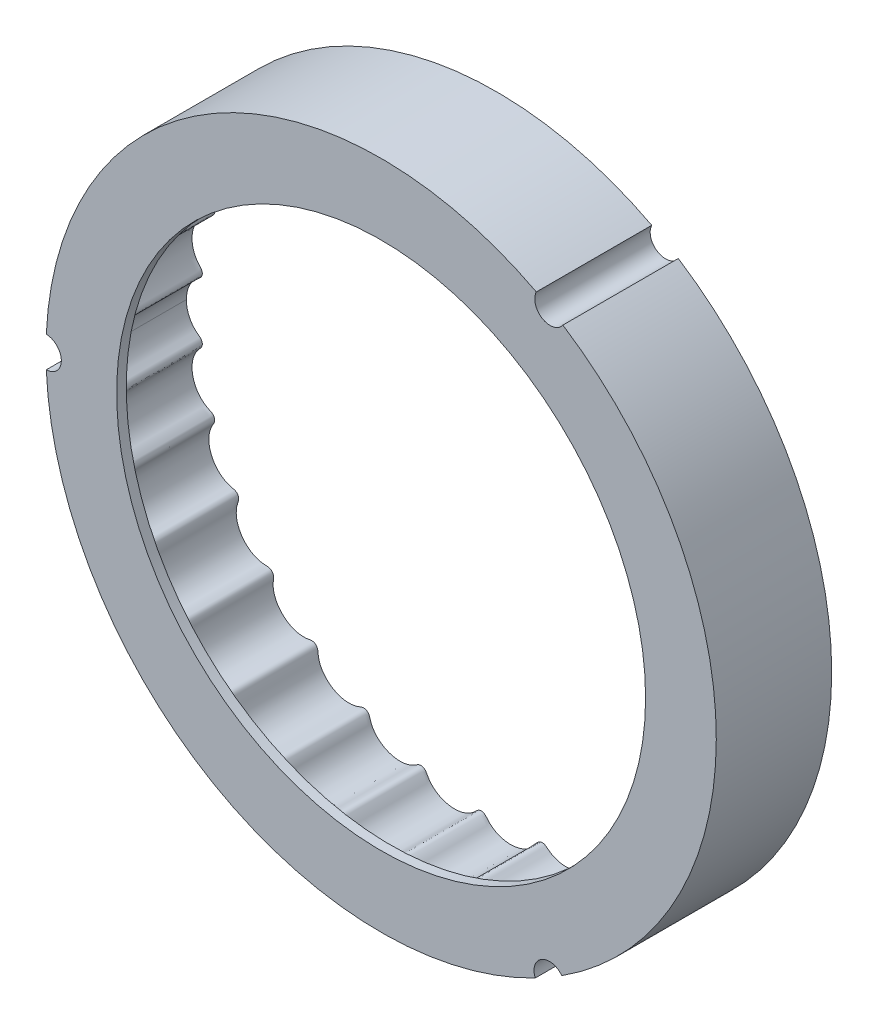
SolidWorks part; units mm, degrees
ref_plane "Plan de face" through (0, 0, 0) normal (0, 0, 1) x (1, 0, 0)
ref_plane "Plan de dessus" through (0, 0, 0) normal (0, 1, 0) x (1, 0, 0)
ref_plane "Plan de droite" through (0, 0, 0) normal (1, 0, 0) x (0, 0, -1)
sketch "Esquisse1" plane through (0, 0, 0) normal (0, 0, 1) x (1, 0, 0)
  line L0 (-1000, 0) -> (49000, 0) construction
  circle A1 centre (0, 0) radius 34.85
  spline S0 degree 4 poles (30.9263, 8.5917) (30.9244, 8.4726) (30.9128, 8.294) (30.8795, 8.0576) (30.8075, 7.7682) (30.7313, 7.5422) (30.6363, 7.3233) (30.5223, 7.1138) (30.4005, 6.9287) (30.2778, 6.7655) (30.1754, 6.608) (30.1146, 6.4469) (30.0971, 6.2542) (30.1421, 6.0755) (30.2337, 5.9301) (30.3636, 5.8076) (30.4814, 5.7308) (30.5967, 5.6632) (30.7272, 5.5824) (30.8546, 5.4968) (31.0375, 5.3568) (31.2617, 5.1464) (31.5493, 4.8022) (31.8437, 4.2901) (32.0606, 3.6436) (32.1377, 2.876) (32.0537, 2.1997) (31.8673, 1.6401) (31.6545, 1.2467) (31.4775, 0.9968) (31.3101, 0.8048) (31.1655, 0.661) (31.0397, 0.5491) (30.944, 0.4561) (30.882, 0.3799) (30.8461, 0.3281) (30.8149, 0.2732) (30.7893, 0.2154) (30.772, 0.1642) (30.7612, 0.1176) (30.7537, 0.0676) (30.7495, 0.0174) (30.7494, -0.0196) (30.7554, -0.0873) (30.767, -0.1466) (30.7842, -0.2016) (30.8067, -0.2559) (30.8409, -0.3211) (30.8874, -0.3891) (30.9471, -0.4581) (31.0185, -0.528) (31.0876, -0.5916) (31.174, -0.6713) (31.275, -0.7696) (31.4187, -0.925) (31.5905, -1.1493) (31.7652, -1.4406) (31.9227, -1.8045) (32.035, -2.1949) (32.0985, -2.6058) (32.1109, -3.0185) (32.074, -3.4266) (31.9897, -3.8245) (31.8596, -4.2068) (31.6858, -4.5663) (31.471, -4.8977) (31.2491, -5.1584) (31.0376, -5.3559) (30.847, -5.5028) (30.6865, -5.6097) (30.5113, -5.713) (30.3279, -5.8265) (30.1731, -5.9986) (30.0932, -6.2291) (30.1102, -6.46) (30.2005, -6.6565) (30.3192, -6.8188) (30.4296, -6.9724) (30.5569, -7.1717) (30.687, -7.4243) (30.8105, -7.7521) (30.9023, -8.158) (30.9393, -8.591) (30.9154, -9.0432) (30.8331, -9.4792) (30.6986, -9.8922) (30.5175, -10.2769) (30.2954, -10.6287) (30.0366, -10.942) (29.747, -11.2129) (29.4704, -11.4101) (29.2233, -11.5472) (29.008, -11.6414) (28.8315, -11.7068) (28.6421, -11.7692) (28.45, -11.8631) (28.2883, -12.027) (28.2103, -12.2249) (28.2035, -12.4054) (28.2368, -12.5701) (28.2938, -12.7158) (28.368, -12.8732) (28.4417, -13.0514) (28.5193, -13.2794) (28.5859, -13.5612) (28.6259, -13.9014) (28.6202, -14.2968) (28.5642, -14.6927) (28.4589, -15.0831) (28.3079, -15.4581) (28.1138, -15.8126) (27.8795, -16.1417) (27.6077, -16.4405) (27.3049, -16.7011) (26.9756, -16.9193) (26.6681, -17.0697) (26.3953, -17.1663) (26.1618, -17.2248) (25.972, -17.2589) (25.7701, -17.2839) (25.5569, -17.3186) (25.349, -17.4213) (25.1897, -17.6061) (25.1202, -17.827) (25.1307, -18.0426) (25.1768, -18.2381) (25.2169, -18.423) (25.254, -18.6564) (25.2723, -18.9399) (25.2546, -19.2896) (25.1768, -19.6983) (25.0382, -20.11) (24.8361, -20.5151) (24.5838, -20.8868) (24.2876, -21.2199) (23.9535, -21.5097) (23.5874, -21.7517) (23.2101, -21.9337) (22.8739, -22.0436) (22.5914, -22.1021) (22.3252, -22.1336) (22.1016, -22.1407) (21.8785, -22.1275) (21.6437, -22.1096) (21.4389, -22.1288) (21.235, -22.2214) (21.0721, -22.3967) (20.993, -22.6129) (20.9856, -22.8294) (20.9927, -23.0328) (20.9891, -23.2256) (20.9691, -23.4656) (20.9175, -23.7504) (20.8184, -24.0782) (20.6555, -24.4384) (20.4463, -24.779) (20.1313, -25.174) (19.6816, -25.5833) (19.1591, -25.8987) (18.5904, -26.1016) (18.1017, -26.1879) (17.7596, -26.203) (17.4709, -26.1826) (17.2335, -26.1428) (17.0458, -26.0984) (16.8505, -26.0411) (16.6399, -25.9918) (16.4106, -26.0101) (16.1979, -26.12) (16.0541, -26.2917) (15.9812, -26.4843) (15.9468, -26.6722) (15.9136, -26.8477) (15.8717, -27.0214) (15.8184, -27.1921) (15.7382, -27.4006) (15.5637, -27.7585) (15.2945, -28.1386) (14.9171, -28.5115) (14.4633, -28.8259) (14.0673, -29.0303) (13.6447, -29.1826) (13.2023, -29.278) (12.7692, -29.3104) (12.354, -29.2847) (12.0109, -29.2154) (11.7407, -29.1278) (11.5237, -29.0341) (11.3545, -28.9495) (11.1772, -28.8554) (10.9723, -28.7881) (10.7409, -28.7959) (10.5202, -28.8997) (10.3654, -29.0728) (10.2765, -29.2698) (10.2021, -29.4592) (10.1221, -29.6346) (10.0078, -29.8465) (9.8467, -30.087) (9.625, -30.3479) (9.2571, -30.6809) (8.748, -31.0055) (8.1785, -31.2248) (7.5795, -31.329) (7.0742, -31.3356) (6.6768, -31.2918) (6.2924, -31.1996) (5.9727, -31.0767) (5.7161, -30.9427) (5.5144, -30.8112) (5.3599, -30.6957) (5.2035, -30.5655) (5.0269, -30.4397) (4.8069, -30.3718) (4.5688, -30.3956) (4.3717, -30.5019) (4.2324, -30.653) (4.1276, -30.8125) (4.0272, -30.9603) (3.9195, -31.1029) (3.8025, -31.238) (3.6457, -31.3971) (3.3428, -31.6554) (2.8502, -31.9535) (2.2369, -32.1596) (1.5733, -32.2322) (1.0155, -32.1965) (0.5716, -32.1077) (0.1613, -31.9647) (-0.2092, -31.7754) (-0.4962, -31.5747) (-0.7089, -31.3863) (-0.8705, -31.2138) (-0.9919, -31.0688) (-1.1186, -30.9128) (-1.2838, -30.7736) (-1.5018, -30.6954) (-1.7453, -30.7105) (-1.9528, -30.8138) (-2.1099, -30.9617) (-2.2535, -31.1059) (-2.3968, -31.2349) (-2.5863, -31.3834) (-2.8299, -31.5395) (-3.1373, -31.6901) (-3.5116, -31.8163) (-3.9031, -31.8956) (-4.3058, -31.9269) (-4.7094, -31.9102) (-5.1084, -31.8461) (-5.4973, -31.7354) (-5.8703, -31.5791) (-6.2174, -31.3804) (-6.5332, -31.1424) (-6.7773, -30.902) (-6.9589, -30.6765) (-7.0914, -30.4753) (-7.1869, -30.3078) (-7.2659, -30.1527) (-7.3469, -30.0188) (-7.4577, -29.8924) (-7.6055, -29.7886) (-7.8103, -29.7311) (-8.0386, -29.7607) (-8.2296, -29.8563) (-8.3948, -29.9679) (-8.5547, -30.0672) (-8.7612, -30.1794) (-9.0211, -30.2905) (-9.3464, -30.3878) (-9.7381, -30.4504) (-10.1442, -30.4625) (-10.5582, -30.4222) (-10.9731, -30.3294) (-11.3818, -30.1823) (-11.7767, -29.98) (-12.1486, -29.7215) (-12.4679, -29.4266) (-12.7322, -29.1051) (-12.9152, -28.8064) (-13.0349, -28.5486) (-13.1142, -28.3258) (-13.1678, -28.1444) (-13.224, -27.9513) (-13.3256, -27.7603) (-13.4992, -27.6071) (-13.731, -27.5313) (-13.9616, -27.5503) (-14.1632, -27.6266) (-14.3522, -27.7017) (-14.535, -27.7628) (-14.7681, -27.8232) (-15.0538, -27.869) (-15.3957, -27.8843) (-15.7892, -27.8507) (-16.2785, -27.7463) (-16.7528, -27.5609) (-17.1946, -27.3015) (-17.5907, -26.9743) (-17.8764, -26.672) (-18.1159, -26.3439) (-18.3067, -25.9962) (-18.4295, -25.6796) (-18.5013, -25.4063) (-18.5394, -25.1743) (-18.559, -24.9871) (-18.5718, -24.7882) (-18.6117, -24.5785) (-18.7262, -24.3789) (-18.8959, -24.2506) (-19.068, -24.1957) (-19.2358, -24.1842) (-19.3915, -24.2014) (-19.5625, -24.2339) (-19.7534, -24.2613) (-19.9935, -24.2801) (-20.283, -24.2751) (-20.6226, -24.2297) (-21.0043, -24.1264) (-21.3741, -23.9741) (-21.7265, -23.7753) (-22.0523, -23.536) (-22.3477, -23.2602) (-22.6084, -22.9516) (-22.8306, -22.6144) (-23.008, -22.2566) (-23.138, -21.8836) (-23.2077, -21.5484) (-23.2339, -21.2603) (-23.2329, -21.0195) (-23.2189, -20.8273) (-23.1931, -20.6255) (-23.1714, -20.4109) (-23.2147, -20.1833) (-23.35, -19.9802) (-23.5441, -19.854) (-23.755, -19.8069) (-23.956, -19.8018) (-24.145, -19.7948) (-24.3804, -19.7731) (-24.6597, -19.7208) (-25.1025, -19.5837) (-25.5719, -19.3339) (-26.0033, -18.993) (-26.3759, -18.5716) (-26.6251, -18.2022) (-26.8231, -17.8067) (-26.9668, -17.3922) (-27.0498, -16.9817) (-27.0732, -16.6288) (-27.06, -16.3406) (-27.0307, -16.1192) (-26.9958, -15.9439) (-26.9493, -15.7714) (-26.894, -15.6014) (-26.8318, -15.421) (-26.7962, -15.2188) (-26.8307, -14.9976) (-26.9558, -14.7937) (-27.1431, -14.6595) (-27.3504, -14.5957) (-27.5492, -14.5518) (-27.7351, -14.5006) (-27.9627, -14.422) (-28.2261, -14.3016) (-28.5192, -14.1246) (-28.8279, -13.8775) (-29.1063, -13.5905) (-29.4109, -13.1873) (-29.6486, -12.7398) (-29.8135, -12.2607) (-29.9002, -11.7631) (-29.9203, -11.3641) (-29.8906, -10.9701) (-29.8207, -10.6349) (-29.7296, -10.3602) (-29.6324, -10.14) (-29.543, -9.9692) (-29.4389, -9.7943) (-29.3367, -9.6039) (-29.2926, -9.3762) (-29.3434, -9.1376) (-29.4773, -8.9486) (-29.655, -8.8263) (-29.838, -8.7434) (-30.0085, -8.6617) (-30.2156, -8.5478) (-30.4507, -8.3882) (-30.716, -8.1598) (-30.9909, -7.8477) (-31.231, -7.4857) (-31.427, -7.0776) (-31.5659, -6.6505) (-31.6473, -6.2122) (-31.6713, -5.7706) (-31.638, -5.3329) (-31.5503, -4.9233) (-31.4308, -4.5902) (-31.3037, -4.3313) (-31.1883, -4.14) (-31.0862, -3.9932) (-30.9747, -3.8536) (-30.8564, -3.7197) (-30.7286, -3.5777) (-30.6197, -3.4032) (-30.57, -3.1848) (-30.6111, -2.949) (-30.7353, -2.7553) (-30.9027, -2.6179) (-31.0677, -2.4988) (-31.2178, -2.3777) (-31.395, -2.2147) (-31.5882, -1.9992) (-31.757, -1.7611) (-31.8999, -1.5043) (-32.0017, -1.2787) (-32.0729, -1.0898) (-32.1322, -0.8972) (-32.1797, -0.7008) (-32.2109, -0.5276) (-32.2302, -0.3771) (-32.2413, -0.2512) (-32.2473, -0.1576) (-32.2503, -0.0299) (-32.2502, 0.0388) (-32.2466, 0.1794) (-32.2393, 0.2769) (-32.2254, 0.4211) (-32.2015, 0.5861) (-32.1629, 0.7796) (-32.104, 0.996) (-32.0305, 1.2085) (-31.9423, 1.415) (-31.8234, 1.6465) (-31.6896, 1.8577) (-31.544, 2.0481) (-31.3892, 2.217) (-31.2566, 2.3437) (-31.1158, 2.461) (-30.9692, 2.571) (-30.8116, 2.6874) (-30.6684, 2.8431) (-30.5791, 3.0569) (-30.5824, 3.2743) (-30.648, 3.4491) (-30.7462, 3.5961) (-30.8554, 3.7195) (-30.9782, 3.8564) (-31.1043, 4.0167) (-31.2467, 4.228) (-31.3916, 4.4977) (-31.5524, 4.9075) (-31.6691, 5.4709) (-31.6776, 6.1306) (-31.5281, 6.8579) (-31.2314, 7.526) (-30.8027, 8.104) (-30.3929, 8.4476) (-30.0923, 8.62) (-29.937, 8.6951) knots 0 0 0 0 0 0.003562 0.005342 0.007123 0.008904 0.010685 0.012466 0.014247 0.015519 0.016792 0.018065 0.019337 0.021229 0.022175 0.02312 0.024649 0.025414 0.026178 0.027707 0.029236 0.032293 0.035351 0.04107 0.046788 0.052507 0.058226 0.06127 0.064314 0.065836 0.067358 0.06888 0.070402 0.070873 0.071343 0.071813 0.072284 0.072754 0.073224 0.073459 0.073695 0.074165 0.074604 0.075042 0.075481 0.07592 0.076358 0.076797 0.077674 0.078377 0.079079 0.079782 0.080484 0.081889 0.083294 0.086104 0.088914 0.092014 0.095114 0.098215 0.101315 0.104325 0.107336 0.110347 0.113357 0.116235 0.119112 0.12055 0.121989 0.123428 0.124866 0.12664 0.128414 0.130187 0.13196 0.133373 0.134786 0.1362 0.137613 0.140439 0.143265 0.146639 0.150014 0.153388 0.156763 0.159865 0.162966 0.166068 0.169169 0.171979 0.174789 0.176194 0.177599 0.179004 0.180409 0.182167 0.183924 0.185706 0.186596 0.187487 0.188927 0.190366 0.191805 0.193245 0.196124 0.199002 0.202017 0.205033 0.208048 0.211063 0.214074 0.217086 0.220098 0.22311 0.225987 0.228865 0.230303 0.231742 0.233181 0.234619 0.236396 0.238172 0.239944 0.241716 0.243129 0.244541 0.245954 0.247367 0.250192 0.253017 0.256391 0.259764 0.263137 0.266511 0.269782 0.273052 0.276323 0.279594 0.282264 0.283598 0.284933 0.287603 0.288938 0.290273 0.291978 0.293684 0.295463 0.297243 0.298682 0.300121 0.30156 0.302999 0.305877 0.308756 0.311769 0.314783 0.317797 0.323824 0.32985 0.332862 0.33574 0.338618 0.340058 0.341497 0.342936 0.344375 0.346152 0.34793 0.349637 0.351344 0.352679 0.354014 0.355349 0.356684 0.358019 0.359354 0.362024 0.368567 0.371839 0.375111 0.378483 0.381856 0.385228 0.388601 0.391426 0.39425 0.395663 0.397075 0.398488 0.3999 0.401672 0.403443 0.40522 0.406997 0.408436 0.409875 0.411314 0.412753 0.415631 0.418509 0.421521 0.427546 0.433573 0.436587 0.439601 0.442616 0.445494 0.448372 0.449812 0.451251 0.45269 0.454129 0.455909 0.457689 0.459394 0.461099 0.462434 0.463768 0.465103 0.466438 0.467773 0.469108 0.471777 0.478318 0.484859 0.488232 0.491606 0.49498 0.498354 0.501179 0.504005 0.505418 0.50683 0.508243 0.509656 0.511429 0.513201 0.514977 0.516752 0.518191 0.519629 0.521068 0.522507 0.525384 0.528261 0.531273 0.534284 0.537295 0.540307 0.543322 0.546338 0.549353 0.552369 0.555248 0.558127 0.559566 0.561006 0.562445 0.563885 0.564776 0.565667 0.567449 0.569206 0.570963 0.572368 0.573772 0.575177 0.576582 0.579392 0.582202 0.585303 0.588404 0.591505 0.594606 0.597981 0.601356 0.604731 0.608106 0.610932 0.613759 0.615172 0.616585 0.617999 0.619412 0.621185 0.622958 0.624731 0.626505 0.627943 0.629382 0.63082 0.632259 0.635136 0.638013 0.641024 0.644034 0.650055 0.653155 0.656256 0.659357 0.662457 0.665267 0.668077 0.669482 0.670887 0.672292 0.673697 0.675453 0.677208 0.678992 0.679883 0.680775 0.682214 0.683654 0.685093 0.686533 0.689412 0.69229 0.695306 0.698322 0.701338 0.704354 0.707365 0.710376 0.713387 0.716398 0.719275 0.722153 0.723591 0.72503 0.726469 0.727907 0.729682 0.731457 0.73323 0.735002 0.736415 0.737828 0.739241 0.740654 0.74348 0.746306 0.753054 0.756428 0.759802 0.763072 0.766342 0.769612 0.772882 0.775551 0.776886 0.778221 0.779556 0.780891 0.782226 0.78356 0.785264 0.786968 0.788749 0.790529 0.791969 0.793408 0.794847 0.796287 0.799165 0.802044 0.805058 0.808073 0.811088 0.817114 0.820127 0.823139 0.826151 0.829028 0.831906 0.833345 0.834784 0.836223 0.837661 0.839438 0.841215 0.842986 0.844758 0.846171 0.847583 0.848996 0.850409 0.853234 0.856059 0.859432 0.862805 0.866178 0.86955 0.872822 0.876093 0.879364 0.882635 0.885305 0.88664 0.887975 0.88931 0.890645 0.89198 0.893315 0.895021 0.896727 0.898506 0.900284 0.901724 0.903163 0.904602 0.906041 0.908919 0.911797 0.913304 0.91481 0.916317 0.917824 0.91933 0.920837 0.92159 0.922344 0.923097 0.92385 0.924689 0.925528 0.926367 0.927206 0.928883 0.930561 0.932238 0.933916 0.935594 0.937271 0.94001 0.941379 0.942748 0.944117 0.945486 0.946856 0.948225 0.949976 0.951727 0.9536 0.954537 0.955474 0.956996 0.958518 0.96004 0.961563 0.964607 0.967651 0.973159 0.978666 0.984174 0.989682 0.994841 1 1 1 1 1 construction
  spline S1 degree 4 poles (30.75, 0) (30.75, -0.0125) (30.751, -0.0374) (30.7554, -0.0873) (30.767, -0.1466) (30.7842, -0.2016) (30.8067, -0.2559) (30.8409, -0.3211) (30.8874, -0.3891) (30.9471, -0.4581) (31.0185, -0.528) (31.0876, -0.5916) (31.174, -0.6713) (31.275, -0.7696) (31.4187, -0.925) (31.5905, -1.1493) (31.7652, -1.4406) (31.9227, -1.8045) (32.035, -2.1949) (32.0985, -2.6058) (32.1109, -3.0185) (32.074, -3.4266) (31.9897, -3.8245) (31.8596, -4.2068) (31.6858, -4.5663) (31.471, -4.8977) (31.2491, -5.1584) (31.0376, -5.3559) (30.847, -5.5028) (30.6865, -5.6097) (30.5113, -5.713) (30.3279, -5.8265) (30.1731, -5.9986) (30.0932, -6.2291) (30.1102, -6.46) (30.2005, -6.6565) (30.3192, -6.8188) (30.4296, -6.9724) (30.5569, -7.1717) (30.687, -7.4243) (30.8105, -7.7521) (30.9023, -8.158) (30.9393, -8.591) (30.9154, -9.0432) (30.8331, -9.4792) (30.6986, -9.8922) (30.5175, -10.2769) (30.2954, -10.6287) (30.0366, -10.942) (29.747, -11.2129) (29.4704, -11.4101) (29.2233, -11.5472) (29.008, -11.6414) (28.8315, -11.7068) (28.6421, -11.7692) (28.45, -11.8631) (28.2883, -12.027) (28.2103, -12.2249) (28.2035, -12.4054) (28.2368, -12.5701) (28.2938, -12.7158) (28.368, -12.8732) (28.4417, -13.0514) (28.5193, -13.2794) (28.5859, -13.5612) (28.6259, -13.9014) (28.6202, -14.2968) (28.5642, -14.6927) (28.4589, -15.0831) (28.3079, -15.4581) (28.1138, -15.8126) (27.8795, -16.1417) (27.6077, -16.4405) (27.3049, -16.7011) (26.9756, -16.9193) (26.6681, -17.0697) (26.3953, -17.1663) (26.1618, -17.2248) (25.972, -17.2589) (25.7701, -17.2839) (25.5569, -17.3186) (25.349, -17.4213) (25.1897, -17.6061) (25.1202, -17.827) (25.1307, -18.0426) (25.1768, -18.2381) (25.2169, -18.423) (25.254, -18.6564) (25.2723, -18.9399) (25.2546, -19.2896) (25.1768, -19.6983) (25.0382, -20.11) (24.8361, -20.5151) (24.5838, -20.8868) (24.2876, -21.2199) (23.9535, -21.5097) (23.5874, -21.7517) (23.2101, -21.9337) (22.8739, -22.0436) (22.5914, -22.1021) (22.3252, -22.1336) (22.1016, -22.1407) (21.8785, -22.1275) (21.6437, -22.1096) (21.4389, -22.1288) (21.235, -22.2214) (21.0721, -22.3967) (20.993, -22.6129) (20.9856, -22.8294) (20.9927, -23.0328) (20.9891, -23.2256) (20.9691, -23.4656) (20.9175, -23.7504) (20.8184, -24.0782) (20.6555, -24.4384) (20.4463, -24.779) (20.1313, -25.174) (19.6816, -25.5833) (19.1591, -25.8987) (18.5904, -26.1016) (18.1017, -26.1879) (17.7596, -26.203) (17.4709, -26.1826) (17.2335, -26.1428) (17.0458, -26.0984) (16.8505, -26.0411) (16.6399, -25.9918) (16.4106, -26.0101) (16.1979, -26.12) (16.0541, -26.2917) (15.9812, -26.4843) (15.9468, -26.6722) (15.9136, -26.8477) (15.8717, -27.0214) (15.8184, -27.1921) (15.7382, -27.4006) (15.5637, -27.7585) (15.2945, -28.1386) (14.9171, -28.5115) (14.4633, -28.8259) (14.0673, -29.0303) (13.6447, -29.1826) (13.2023, -29.278) (12.7692, -29.3104) (12.354, -29.2847) (12.0109, -29.2154) (11.7407, -29.1278) (11.5237, -29.0341) (11.3545, -28.9495) (11.1772, -28.8554) (10.9723, -28.7881) (10.7409, -28.7959) (10.5202, -28.8997) (10.3654, -29.0728) (10.2765, -29.2698) (10.2021, -29.4592) (10.1221, -29.6346) (10.0078, -29.8465) (9.8467, -30.087) (9.625, -30.3479) (9.2571, -30.6809) (8.748, -31.0055) (8.1785, -31.2248) (7.5795, -31.329) (7.0742, -31.3356) (6.6768, -31.2918) (6.2924, -31.1996) (5.9727, -31.0767) (5.7161, -30.9427) (5.5144, -30.8112) (5.3599, -30.6957) (5.2035, -30.5655) (5.0269, -30.4397) (4.8069, -30.3718) (4.5688, -30.3956) (4.3717, -30.5019) (4.2324, -30.653) (4.1276, -30.8125) (4.0272, -30.9603) (3.9195, -31.1029) (3.8025, -31.238) (3.6457, -31.3971) (3.3428, -31.6554) (2.8502, -31.9535) (2.2369, -32.1596) (1.5733, -32.2322) (1.0155, -32.1965) (0.5716, -32.1077) (0.1613, -31.9647) (-0.2092, -31.7754) (-0.4962, -31.5747) (-0.7089, -31.3863) (-0.8705, -31.2138) (-0.9919, -31.0688) (-1.1186, -30.9128) (-1.2838, -30.7736) (-1.5018, -30.6954) (-1.7453, -30.7105) (-1.9528, -30.8138) (-2.1099, -30.9617) (-2.2535, -31.1059) (-2.3968, -31.2349) (-2.5863, -31.3834) (-2.8299, -31.5395) (-3.1373, -31.6901) (-3.5116, -31.8163) (-3.9031, -31.8956) (-4.3058, -31.9269) (-4.7094, -31.9102) (-5.1084, -31.8461) (-5.4973, -31.7354) (-5.8703, -31.5791) (-6.2174, -31.3804) (-6.5332, -31.1424) (-6.7773, -30.902) (-6.9589, -30.6765) (-7.0914, -30.4753) (-7.1869, -30.3078) (-7.2659, -30.1527) (-7.3469, -30.0188) (-7.4577, -29.8924) (-7.6055, -29.7886) (-7.8103, -29.7311) (-8.0386, -29.7607) (-8.2296, -29.8563) (-8.3948, -29.9679) (-8.5547, -30.0672) (-8.7612, -30.1794) (-9.0211, -30.2905) (-9.3464, -30.3878) (-9.7381, -30.4504) (-10.1442, -30.4625) (-10.5582, -30.4222) (-10.9731, -30.3294) (-11.3818, -30.1823) (-11.7767, -29.98) (-12.1486, -29.7215) (-12.4679, -29.4266) (-12.7322, -29.1051) (-12.9152, -28.8064) (-13.0349, -28.5486) (-13.1142, -28.3258) (-13.1678, -28.1444) (-13.224, -27.9513) (-13.3256, -27.7603) (-13.4992, -27.6071) (-13.731, -27.5313) (-13.9616, -27.5503) (-14.1632, -27.6266) (-14.3522, -27.7017) (-14.535, -27.7628) (-14.7681, -27.8232) (-15.0538, -27.869) (-15.3957, -27.8843) (-15.7892, -27.8507) (-16.2785, -27.7463) (-16.7528, -27.5609) (-17.1946, -27.3015) (-17.5907, -26.9743) (-17.8764, -26.672) (-18.1159, -26.3439) (-18.3067, -25.9962) (-18.4295, -25.6796) (-18.5013, -25.4063) (-18.5394, -25.1743) (-18.559, -24.9871) (-18.5718, -24.7882) (-18.6117, -24.5785) (-18.7262, -24.3789) (-18.8959, -24.2506) (-19.068, -24.1957) (-19.2358, -24.1842) (-19.3915, -24.2014) (-19.5625, -24.2339) (-19.7534, -24.2613) (-19.9935, -24.2801) (-20.283, -24.2751) (-20.6226, -24.2297) (-21.0043, -24.1264) (-21.3741, -23.9741) (-21.7265, -23.7753) (-22.0523, -23.536) (-22.3477, -23.2602) (-22.6084, -22.9516) (-22.8306, -22.6144) (-23.008, -22.2566) (-23.138, -21.8836) (-23.2077, -21.5484) (-23.2339, -21.2603) (-23.2329, -21.0195) (-23.2189, -20.8273) (-23.1931, -20.6255) (-23.1714, -20.4109) (-23.2147, -20.1833) (-23.35, -19.9802) (-23.5441, -19.854) (-23.755, -19.8069) (-23.956, -19.8018) (-24.145, -19.7948) (-24.3804, -19.7731) (-24.6597, -19.7208) (-25.1025, -19.5837) (-25.5719, -19.3339) (-26.0033, -18.993) (-26.3759, -18.5716) (-26.6251, -18.2022) (-26.8231, -17.8067) (-26.9668, -17.3922) (-27.0498, -16.9817) (-27.0732, -16.6288) (-27.06, -16.3406) (-27.0307, -16.1192) (-26.9958, -15.9439) (-26.9493, -15.7714) (-26.894, -15.6014) (-26.8318, -15.421) (-26.7962, -15.2188) (-26.8307, -14.9976) (-26.9558, -14.7937) (-27.1431, -14.6595) (-27.3504, -14.5957) (-27.5492, -14.5518) (-27.7351, -14.5006) (-27.9627, -14.422) (-28.2261, -14.3016) (-28.5192, -14.1246) (-28.8279, -13.8775) (-29.1063, -13.5905) (-29.4109, -13.1873) (-29.6486, -12.7398) (-29.8135, -12.2607) (-29.9002, -11.7631) (-29.9203, -11.3641) (-29.8906, -10.9701) (-29.8207, -10.6349) (-29.7296, -10.3602) (-29.6324, -10.14) (-29.543, -9.9692) (-29.4389, -9.7943) (-29.3367, -9.6039) (-29.2926, -9.3762) (-29.3434, -9.1376) (-29.4773, -8.9486) (-29.655, -8.8263) (-29.838, -8.7434) (-30.0085, -8.6617) (-30.2156, -8.5478) (-30.4507, -8.3882) (-30.716, -8.1598) (-30.9909, -7.8477) (-31.231, -7.4857) (-31.427, -7.0776) (-31.5659, -6.6505) (-31.6473, -6.2122) (-31.6713, -5.7706) (-31.638, -5.3329) (-31.5503, -4.9233) (-31.4308, -4.5902) (-31.3037, -4.3313) (-31.1883, -4.14) (-31.0862, -3.9932) (-30.9747, -3.8536) (-30.8564, -3.7197) (-30.7286, -3.5777) (-30.6197, -3.4032) (-30.57, -3.1848) (-30.6111, -2.949) (-30.7353, -2.7553) (-30.9027, -2.6179) (-31.0677, -2.4988) (-31.2178, -2.3777) (-31.395, -2.2147) (-31.5882, -1.9992) (-31.757, -1.7611) (-31.8999, -1.5043) (-32.0017, -1.2787) (-32.0729, -1.0898) (-32.1322, -0.8972) (-32.1797, -0.7008) (-32.2109, -0.5276) (-32.2302, -0.3771) (-32.2413, -0.2512) (-32.2473, -0.1576) (-32.2495, -0.0645) (-32.25, -0.0214) (-32.25, 0) knots 0.074165 0.074165 0.074165 0.074165 0.074165 0.074604 0.075042 0.075481 0.07592 0.076358 0.076797 0.077674 0.078377 0.079079 0.079782 0.080484 0.081889 0.083294 0.086104 0.088914 0.092014 0.095114 0.098215 0.101315 0.104325 0.107336 0.110347 0.113357 0.116235 0.119112 0.12055 0.121989 0.123428 0.124866 0.12664 0.128414 0.130187 0.13196 0.133373 0.134786 0.1362 0.137613 0.140439 0.143265 0.146639 0.150014 0.153388 0.156763 0.159865 0.162966 0.166068 0.169169 0.171979 0.174789 0.176194 0.177599 0.179004 0.180409 0.182167 0.183924 0.185706 0.186596 0.187487 0.188927 0.190366 0.191805 0.193245 0.196124 0.199002 0.202017 0.205033 0.208048 0.211063 0.214074 0.217086 0.220098 0.22311 0.225987 0.228865 0.230303 0.231742 0.233181 0.234619 0.236396 0.238172 0.239944 0.241716 0.243129 0.244541 0.245954 0.247367 0.250192 0.253017 0.256391 0.259764 0.263137 0.266511 0.269782 0.273052 0.276323 0.279594 0.282264 0.283598 0.284933 0.287603 0.288938 0.290273 0.291978 0.293684 0.295463 0.297243 0.298682 0.300121 0.30156 0.302999 0.305877 0.308756 0.311769 0.314783 0.317797 0.323824 0.32985 0.332862 0.33574 0.338618 0.340058 0.341497 0.342936 0.344375 0.346152 0.34793 0.349637 0.351344 0.352679 0.354014 0.355349 0.356684 0.358019 0.359354 0.362024 0.368567 0.371839 0.375111 0.378483 0.381856 0.385228 0.388601 0.391426 0.39425 0.395663 0.397075 0.398488 0.3999 0.401672 0.403443 0.40522 0.406997 0.408436 0.409875 0.411314 0.412753 0.415631 0.418509 0.421521 0.427546 0.433573 0.436587 0.439601 0.442616 0.445494 0.448372 0.449812 0.451251 0.45269 0.454129 0.455909 0.457689 0.459394 0.461099 0.462434 0.463768 0.465103 0.466438 0.467773 0.469108 0.471777 0.478318 0.484859 0.488232 0.491606 0.49498 0.498354 0.501179 0.504005 0.505418 0.50683 0.508243 0.509656 0.511429 0.513201 0.514977 0.516752 0.518191 0.519629 0.521068 0.522507 0.525384 0.528261 0.531273 0.534284 0.537295 0.540307 0.543322 0.546338 0.549353 0.552369 0.555248 0.558127 0.559566 0.561006 0.562445 0.563885 0.564776 0.565667 0.567449 0.569206 0.570963 0.572368 0.573772 0.575177 0.576582 0.579392 0.582202 0.585303 0.588404 0.591505 0.594606 0.597981 0.601356 0.604731 0.608106 0.610932 0.613759 0.615172 0.616585 0.617999 0.619412 0.621185 0.622958 0.624731 0.626505 0.627943 0.629382 0.63082 0.632259 0.635136 0.638013 0.641024 0.644034 0.650055 0.653155 0.656256 0.659357 0.662457 0.665267 0.668077 0.669482 0.670887 0.672292 0.673697 0.675453 0.677208 0.678992 0.679883 0.680775 0.682214 0.683654 0.685093 0.686533 0.689412 0.69229 0.695306 0.698322 0.701338 0.704354 0.707365 0.710376 0.713387 0.716398 0.719275 0.722153 0.723591 0.72503 0.726469 0.727907 0.729682 0.731457 0.73323 0.735002 0.736415 0.737828 0.739241 0.740654 0.74348 0.746306 0.753054 0.756428 0.759802 0.763072 0.766342 0.769612 0.772882 0.775551 0.776886 0.778221 0.779556 0.780891 0.782226 0.78356 0.785264 0.786968 0.788749 0.790529 0.791969 0.793408 0.794847 0.796287 0.799165 0.802044 0.805058 0.808073 0.811088 0.817114 0.820127 0.823139 0.826151 0.829028 0.831906 0.833345 0.834784 0.836223 0.837661 0.839438 0.841215 0.842986 0.844758 0.846171 0.847583 0.848996 0.850409 0.853234 0.856059 0.859432 0.862805 0.866178 0.86955 0.872822 0.876093 0.879364 0.882635 0.885305 0.88664 0.887975 0.88931 0.890645 0.89198 0.893315 0.895021 0.896727 0.898506 0.900284 0.901724 0.903163 0.904602 0.906041 0.908919 0.911797 0.913304 0.91481 0.916317 0.917824 0.91933 0.920837 0.92159 0.922344 0.923097 0.92385 0.92385 0.92385 0.92385 0.92385
  spline S2 degree 4 poles (30.75, 0) (30.75, 0.0125) (30.751, 0.0374) (30.7554, 0.0873) (30.767, 0.1466) (30.7842, 0.2016) (30.8067, 0.2559) (30.8409, 0.3211) (30.8874, 0.3891) (30.9471, 0.4581) (31.0185, 0.528) (31.0876, 0.5916) (31.174, 0.6713) (31.275, 0.7696) (31.4187, 0.925) (31.5905, 1.1493) (31.7652, 1.4406) (31.9227, 1.8045) (32.035, 2.1949) (32.0985, 2.6058) (32.1109, 3.0185) (32.074, 3.4266) (31.9897, 3.8245) (31.8596, 4.2068) (31.6858, 4.5663) (31.471, 4.8977) (31.2491, 5.1584) (31.0376, 5.3559) (30.847, 5.5028) (30.6865, 5.6097) (30.5113, 5.713) (30.3279, 5.8265) (30.1731, 5.9986) (30.0932, 6.2291) (30.1102, 6.46) (30.2005, 6.6565) (30.3192, 6.8188) (30.4296, 6.9724) (30.5569, 7.1717) (30.687, 7.4243) (30.8105, 7.7521) (30.9023, 8.158) (30.9393, 8.591) (30.9154, 9.0432) (30.8331, 9.4792) (30.6986, 9.8922) (30.5175, 10.2769) (30.2954, 10.6287) (30.0366, 10.942) (29.747, 11.2129) (29.4704, 11.4101) (29.2233, 11.5472) (29.008, 11.6414) (28.8315, 11.7068) (28.6421, 11.7692) (28.45, 11.8631) (28.2883, 12.027) (28.2103, 12.2249) (28.2035, 12.4054) (28.2368, 12.5701) (28.2938, 12.7158) (28.368, 12.8732) (28.4417, 13.0514) (28.5193, 13.2794) (28.5859, 13.5612) (28.6259, 13.9014) (28.6202, 14.2968) (28.5642, 14.6927) (28.4589, 15.0831) (28.3079, 15.4581) (28.1138, 15.8126) (27.8795, 16.1417) (27.6077, 16.4405) (27.3049, 16.7011) (26.9756, 16.9193) (26.6681, 17.0697) (26.3953, 17.1663) (26.1618, 17.2248) (25.972, 17.2589) (25.7701, 17.2839) (25.5569, 17.3186) (25.349, 17.4213) (25.1897, 17.6061) (25.1202, 17.827) (25.1307, 18.0426) (25.1768, 18.2381) (25.2169, 18.423) (25.254, 18.6564) (25.2723, 18.9399) (25.2546, 19.2896) (25.1768, 19.6983) (25.0382, 20.11) (24.8361, 20.5151) (24.5838, 20.8868) (24.2876, 21.2199) (23.9535, 21.5097) (23.5874, 21.7517) (23.2101, 21.9337) (22.8739, 22.0436) (22.5914, 22.1021) (22.3252, 22.1336) (22.1016, 22.1407) (21.8785, 22.1275) (21.6437, 22.1096) (21.4389, 22.1288) (21.235, 22.2214) (21.0721, 22.3967) (20.993, 22.6129) (20.9856, 22.8294) (20.9927, 23.0328) (20.9891, 23.2256) (20.9691, 23.4656) (20.9175, 23.7504) (20.8184, 24.0782) (20.6555, 24.4384) (20.4463, 24.779) (20.1313, 25.174) (19.6816, 25.5833) (19.1591, 25.8987) (18.5904, 26.1016) (18.1017, 26.1879) (17.7596, 26.203) (17.4709, 26.1826) (17.2335, 26.1428) (17.0458, 26.0984) (16.8505, 26.0411) (16.6399, 25.9918) (16.4106, 26.0101) (16.1979, 26.12) (16.0541, 26.2917) (15.9812, 26.4843) (15.9468, 26.6722) (15.9136, 26.8477) (15.8717, 27.0214) (15.8184, 27.1921) (15.7382, 27.4006) (15.5637, 27.7585) (15.2945, 28.1386) (14.9171, 28.5115) (14.4633, 28.8259) (14.0673, 29.0303) (13.6447, 29.1826) (13.2023, 29.278) (12.7692, 29.3104) (12.354, 29.2847) (12.0109, 29.2154) (11.7407, 29.1278) (11.5237, 29.0341) (11.3545, 28.9495) (11.1772, 28.8554) (10.9723, 28.7881) (10.7409, 28.7959) (10.5202, 28.8997) (10.3654, 29.0728) (10.2765, 29.2698) (10.2021, 29.4592) (10.1221, 29.6346) (10.0078, 29.8465) (9.8467, 30.087) (9.625, 30.3479) (9.2571, 30.6809) (8.748, 31.0055) (8.1785, 31.2248) (7.5795, 31.329) (7.0742, 31.3356) (6.6768, 31.2918) (6.2924, 31.1996) (5.9727, 31.0767) (5.7161, 30.9427) (5.5144, 30.8112) (5.3599, 30.6957) (5.2035, 30.5655) (5.0269, 30.4397) (4.8069, 30.3718) (4.5688, 30.3956) (4.3717, 30.5019) (4.2324, 30.653) (4.1276, 30.8125) (4.0272, 30.9603) (3.9195, 31.1029) (3.8025, 31.238) (3.6457, 31.3971) (3.3428, 31.6554) (2.8502, 31.9535) (2.2369, 32.1596) (1.5733, 32.2322) (1.0155, 32.1965) (0.5716, 32.1077) (0.1613, 31.9647) (-0.2092, 31.7754) (-0.4962, 31.5747) (-0.7089, 31.3863) (-0.8705, 31.2138) (-0.9919, 31.0688) (-1.1186, 30.9128) (-1.2838, 30.7736) (-1.5018, 30.6954) (-1.7453, 30.7105) (-1.9528, 30.8138) (-2.1099, 30.9617) (-2.2535, 31.1059) (-2.3968, 31.2349) (-2.5863, 31.3834) (-2.8299, 31.5395) (-3.1373, 31.6901) (-3.5116, 31.8163) (-3.9031, 31.8956) (-4.3058, 31.9269) (-4.7094, 31.9102) (-5.1084, 31.8461) (-5.4973, 31.7354) (-5.8703, 31.5791) (-6.2174, 31.3804) (-6.5332, 31.1424) (-6.7773, 30.902) (-6.9589, 30.6765) (-7.0914, 30.4753) (-7.1869, 30.3078) (-7.2659, 30.1527) (-7.3469, 30.0188) (-7.4577, 29.8924) (-7.6055, 29.7886) (-7.8103, 29.7311) (-8.0386, 29.7607) (-8.2296, 29.8563) (-8.3948, 29.9679) (-8.5547, 30.0672) (-8.7612, 30.1794) (-9.0211, 30.2905) (-9.3464, 30.3878) (-9.7381, 30.4504) (-10.1442, 30.4625) (-10.5582, 30.4222) (-10.9731, 30.3294) (-11.3818, 30.1823) (-11.7767, 29.98) (-12.1486, 29.7215) (-12.4679, 29.4266) (-12.7322, 29.1051) (-12.9152, 28.8064) (-13.0349, 28.5486) (-13.1142, 28.3258) (-13.1678, 28.1444) (-13.224, 27.9513) (-13.3256, 27.7603) (-13.4992, 27.6071) (-13.731, 27.5313) (-13.9616, 27.5503) (-14.1632, 27.6266) (-14.3522, 27.7017) (-14.535, 27.7628) (-14.7681, 27.8232) (-15.0538, 27.869) (-15.3957, 27.8843) (-15.7892, 27.8507) (-16.2785, 27.7463) (-16.7528, 27.5609) (-17.1946, 27.3015) (-17.5907, 26.9743) (-17.8764, 26.672) (-18.1159, 26.3439) (-18.3067, 25.9962) (-18.4295, 25.6796) (-18.5013, 25.4063) (-18.5394, 25.1743) (-18.559, 24.9871) (-18.5718, 24.7882) (-18.6117, 24.5785) (-18.7262, 24.3789) (-18.8959, 24.2506) (-19.068, 24.1957) (-19.2358, 24.1842) (-19.3915, 24.2014) (-19.5625, 24.2339) (-19.7534, 24.2613) (-19.9935, 24.2801) (-20.283, 24.2751) (-20.6226, 24.2297) (-21.0043, 24.1264) (-21.3741, 23.9741) (-21.7265, 23.7753) (-22.0523, 23.536) (-22.3477, 23.2602) (-22.6084, 22.9516) (-22.8306, 22.6144) (-23.008, 22.2566) (-23.138, 21.8836) (-23.2077, 21.5484) (-23.2339, 21.2603) (-23.2329, 21.0195) (-23.2189, 20.8273) (-23.1931, 20.6255) (-23.1714, 20.4109) (-23.2147, 20.1833) (-23.35, 19.9802) (-23.5441, 19.854) (-23.755, 19.8069) (-23.956, 19.8018) (-24.145, 19.7948) (-24.3804, 19.7731) (-24.6597, 19.7208) (-25.1025, 19.5837) (-25.5719, 19.3339) (-26.0033, 18.993) (-26.3759, 18.5716) (-26.6251, 18.2022) (-26.8231, 17.8067) (-26.9668, 17.3922) (-27.0498, 16.9817) (-27.0732, 16.6288) (-27.06, 16.3406) (-27.0307, 16.1192) (-26.9958, 15.9439) (-26.9493, 15.7714) (-26.894, 15.6014) (-26.8318, 15.421) (-26.7962, 15.2188) (-26.8307, 14.9976) (-26.9558, 14.7937) (-27.1431, 14.6595) (-27.3504, 14.5957) (-27.5492, 14.5518) (-27.7351, 14.5006) (-27.9627, 14.422) (-28.2261, 14.3016) (-28.5192, 14.1246) (-28.8279, 13.8775) (-29.1063, 13.5905) (-29.4109, 13.1873) (-29.6486, 12.7398) (-29.8135, 12.2607) (-29.9002, 11.7631) (-29.9203, 11.3641) (-29.8906, 10.9701) (-29.8207, 10.6349) (-29.7296, 10.3602) (-29.6324, 10.14) (-29.543, 9.9692) (-29.4389, 9.7943) (-29.3367, 9.6039) (-29.2926, 9.3762) (-29.3434, 9.1376) (-29.4773, 8.9486) (-29.655, 8.8263) (-29.838, 8.7434) (-30.0085, 8.6617) (-30.2156, 8.5478) (-30.4507, 8.3882) (-30.716, 8.1598) (-30.9909, 7.8477) (-31.231, 7.4857) (-31.427, 7.0776) (-31.5659, 6.6505) (-31.6473, 6.2122) (-31.6713, 5.7706) (-31.638, 5.3329) (-31.5503, 4.9233) (-31.4308, 4.5902) (-31.3037, 4.3313) (-31.1883, 4.14) (-31.0862, 3.9932) (-30.9747, 3.8536) (-30.8564, 3.7197) (-30.7286, 3.5777) (-30.6197, 3.4032) (-30.57, 3.1848) (-30.6111, 2.949) (-30.7353, 2.7553) (-30.9027, 2.6179) (-31.0677, 2.4988) (-31.2178, 2.3777) (-31.395, 2.2147) (-31.5882, 1.9992) (-31.757, 1.7611) (-31.8999, 1.5043) (-32.0017, 1.2787) (-32.0729, 1.0898) (-32.1322, 0.8972) (-32.1797, 0.7008) (-32.2109, 0.5276) (-32.2302, 0.3771) (-32.2413, 0.2512) (-32.2473, 0.1576) (-32.2495, 0.0645) (-32.25, 0.0214) (-32.25, 0) knots 0.074165 0.074165 0.074165 0.074165 0.074165 0.074604 0.075042 0.075481 0.07592 0.076358 0.076797 0.077674 0.078377 0.079079 0.079782 0.080484 0.081889 0.083294 0.086104 0.088914 0.092014 0.095114 0.098215 0.101315 0.104325 0.107336 0.110347 0.113357 0.116235 0.119112 0.12055 0.121989 0.123428 0.124866 0.12664 0.128414 0.130187 0.13196 0.133373 0.134786 0.1362 0.137613 0.140439 0.143265 0.146639 0.150014 0.153388 0.156763 0.159865 0.162966 0.166068 0.169169 0.171979 0.174789 0.176194 0.177599 0.179004 0.180409 0.182167 0.183924 0.185706 0.186596 0.187487 0.188927 0.190366 0.191805 0.193245 0.196124 0.199002 0.202017 0.205033 0.208048 0.211063 0.214074 0.217086 0.220098 0.22311 0.225987 0.228865 0.230303 0.231742 0.233181 0.234619 0.236396 0.238172 0.239944 0.241716 0.243129 0.244541 0.245954 0.247367 0.250192 0.253017 0.256391 0.259764 0.263137 0.266511 0.269782 0.273052 0.276323 0.279594 0.282264 0.283598 0.284933 0.287603 0.288938 0.290273 0.291978 0.293684 0.295463 0.297243 0.298682 0.300121 0.30156 0.302999 0.305877 0.308756 0.311769 0.314783 0.317797 0.323824 0.32985 0.332862 0.33574 0.338618 0.340058 0.341497 0.342936 0.344375 0.346152 0.34793 0.349637 0.351344 0.352679 0.354014 0.355349 0.356684 0.358019 0.359354 0.362024 0.368567 0.371839 0.375111 0.378483 0.381856 0.385228 0.388601 0.391426 0.39425 0.395663 0.397075 0.398488 0.3999 0.401672 0.403443 0.40522 0.406997 0.408436 0.409875 0.411314 0.412753 0.415631 0.418509 0.421521 0.427546 0.433573 0.436587 0.439601 0.442616 0.445494 0.448372 0.449812 0.451251 0.45269 0.454129 0.455909 0.457689 0.459394 0.461099 0.462434 0.463768 0.465103 0.466438 0.467773 0.469108 0.471777 0.478318 0.484859 0.488232 0.491606 0.49498 0.498354 0.501179 0.504005 0.505418 0.50683 0.508243 0.509656 0.511429 0.513201 0.514977 0.516752 0.518191 0.519629 0.521068 0.522507 0.525384 0.528261 0.531273 0.534284 0.537295 0.540307 0.543322 0.546338 0.549353 0.552369 0.555248 0.558127 0.559566 0.561006 0.562445 0.563885 0.564776 0.565667 0.567449 0.569206 0.570963 0.572368 0.573772 0.575177 0.576582 0.579392 0.582202 0.585303 0.588404 0.591505 0.594606 0.597981 0.601356 0.604731 0.608106 0.610932 0.613759 0.615172 0.616585 0.617999 0.619412 0.621185 0.622958 0.624731 0.626505 0.627943 0.629382 0.63082 0.632259 0.635136 0.638013 0.641024 0.644034 0.650055 0.653155 0.656256 0.659357 0.662457 0.665267 0.668077 0.669482 0.670887 0.672292 0.673697 0.675453 0.677208 0.678992 0.679883 0.680775 0.682214 0.683654 0.685093 0.686533 0.689412 0.69229 0.695306 0.698322 0.701338 0.704354 0.707365 0.710376 0.713387 0.716398 0.719275 0.722153 0.723591 0.72503 0.726469 0.727907 0.729682 0.731457 0.73323 0.735002 0.736415 0.737828 0.739241 0.740654 0.74348 0.746306 0.753054 0.756428 0.759802 0.763072 0.766342 0.769612 0.772882 0.775551 0.776886 0.778221 0.779556 0.780891 0.782226 0.78356 0.785264 0.786968 0.788749 0.790529 0.791969 0.793408 0.794847 0.796287 0.799165 0.802044 0.805058 0.808073 0.811088 0.817114 0.820127 0.823139 0.826151 0.829028 0.831906 0.833345 0.834784 0.836223 0.837661 0.839438 0.841215 0.842986 0.844758 0.846171 0.847583 0.848996 0.850409 0.853234 0.856059 0.859432 0.862805 0.866178 0.86955 0.872822 0.876093 0.879364 0.882635 0.885305 0.88664 0.887975 0.88931 0.890645 0.89198 0.893315 0.895021 0.896727 0.898506 0.900284 0.901724 0.903163 0.904602 0.906041 0.908919 0.911797 0.913304 0.91481 0.916317 0.917824 0.91933 0.920837 0.92159 0.922344 0.923097 0.92385 0.92385 0.92385 0.92385 0.92385
  dimension "D1" = 69.7
extrude "Boss.-Extru.1" add sketch "Esquisse1" along normal blind 11
sketch "Esquisse3" plane through (0, 0, 11) normal (0, 0, 1) x (1, 0, 0)
  circle A0 centre (0, 0) radius 27.5
  circle A1 centre (0, 0) radius 34.85
  circle A2 centre (0, 0) radius 34.85 construction
  dimension "D1" = 55
extrude "Boss.-Extru.2" add sketch "Esquisse3" along normal blind 1
sketch "Esquisse4" plane through (0, 0, 12) normal (0, 0, 1) x (1, 0, 0)
  circle A0 centre (-34.85, 0) radius 1.6
  circle A1 centre (0, 0) radius 34.85 construction
  circle A10 centre (17.575, 30.181) radius 1.6
  circle A11 centre (17.5, -30.3109) radius 1.6
  point P11 (0.075, -0.0433)
  dimension "D1" = 3.2
  dimension "D2" = 3
extrude "Enlèv. mat.-Extru.2" cut sketch "Esquisse4" against normal through all
equation "\"R\"= 32'Radius of the rotor"
equation "\"E\"= 0.75'Eccentricity from input shaft to center of rotor"
equation "\"Rr\"= 0.5'Roller radius"
equation "\"N\"= 32'Amount of rollers"
